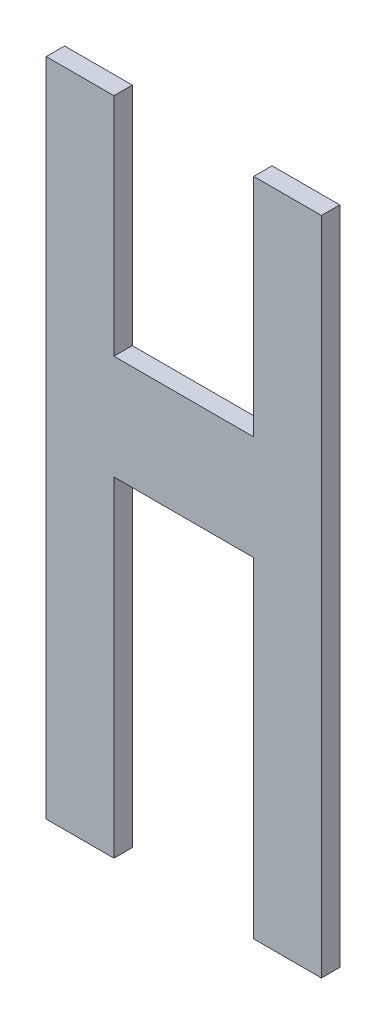
SolidWorks part; units mm, degrees
ref_plane "Front Plane" through (0, 0, 0) normal (0, 0, 1) x (1, 0, 0)
ref_plane "Top Plane" through (0, 0, 0) normal (0, 1, 0) x (1, 0, 0)
ref_plane "Right Plane" through (0, 0, 0) normal (1, 0, 0) x (0, 0, -1)
sketch "Sketch1" plane through (0, 0, 0) normal (0, 0, 1) x (1, 0, 0)
  line L0 (-429.5148, 508.4402) -> (-429.5148, -405.9598)
  line L1 (-429.5148, -405.9598) -> (-335.7888, -405.9598)
  line L2 (-335.7888, -405.9598) -> (-335.7888, 51.2402)
  line L3 (-335.7888, 51.2402) -> (-142.2841, 51.2402)
  line L4 (-142.2841, 51.2402) -> (-142.2841, -405.9598)
  line L5 (-142.2841, -405.9598) -> (-48.5148, -405.9598)
  line L6 (-48.5148, -405.9598) -> (-48.5148, 508.4402)
  line L7 (-48.5148, 508.4402) -> (-142.2841, 508.4402)
  line L8 (-142.2841, 508.4402) -> (-142.2841, 196.0202)
  line L9 (-142.2841, 196.0202) -> (-335.7888, 196.0202)
  line L10 (-335.7888, 196.0202) -> (-335.7888, 508.4402)
  line L11 (-335.7888, 508.4402) -> (-429.5148, 508.4402)
  point P12 (0, 0)
  point P13 (0, 0)
  dimension "D1" = 381
  dimension "D2" = 144.78
  dimension "D3" = 914.4
  dimension "D4" = 914.4
  dimension "D5" = 457.2
  dimension "D6" = 0
  dimension "D8" = 93.7693
  dimension "D9" = 93.726
extrude "Boss-Extrude1" add sketch "Sketch1" along normal blind 25.4
